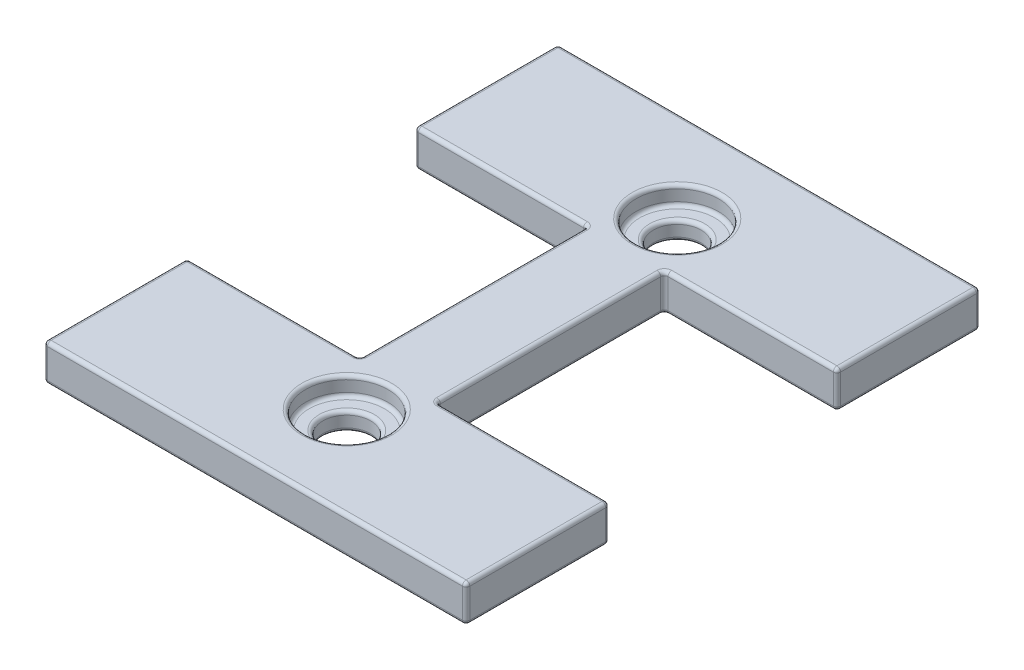
SolidWorks part; units mm, degrees
ref_plane "Front Plane" through (0, 0, 0) normal (0, 0, 1) x (1, 0, 0)
ref_plane "Top Plane" through (0, 0, 0) normal (0, 1, 0) x (1, 0, 0)
ref_plane "Right Plane" through (0, 0, 0) normal (1, 0, 0) x (0, 0, -1)
sketch "Sketch1" plane through (0, 0, 0) normal (0, 1, 0) x (1, 0, 0)
  line L0 (-55, 0) -> (55, 0) construction
  line L1 (-5.75, 7) -> (5.75, 7)
  line L2 (-5.75, 7) -> (-5.75, -7)
  line L3 (-5.75, -7) -> (5.75, -7)
  line L4 (5.75, 7) -> (5.75, -7)
  line L5 (0, -55) -> (0, 55) construction
  dimension "D1" = 14
  dimension "D2" = 7
  dimension "D3" = 11.5
  dimension "D4" = 5.75
extrude "Boss-Extrude1" add sketch "Sketch1" along normal blind 1
sketch "Sketch2" plane through (0, 1, 0) normal (0, 1, 0) x (1, 0, 0)
  line L0 (-0.55, 0) -> (0.55, 0) construction
  line L1 (-9.1867, 3.1) -> (-1.05, 3.1)
  line L2 (-9.1867, 3.1) -> (-9.1867, -3.1)
  line L3 (-9.1867, -3.1) -> (-1.05, -3.1)
  line L4 (-1.05, 3.1) -> (-1.05, -3.1)
  line L5 (1.05, 3.1) -> (10.2161, 3.1)
  line L6 (1.05, 3.1) -> (1.05, -3.1)
  line L7 (1.05, -3.1) -> (10.2161, -3.1)
  line L8 (10.2161, 3.1) -> (10.2161, -3.1)
  line L9 (0, -0.55) -> (0, 0.55) construction
  dimension "D1" = 6.2
  dimension "D2" = 6.2
  dimension "D3" = 3.1
  dimension "D4" = 3.1
  dimension "D5" = 2.1
  dimension "D6" = 1.05
extrude "Cut-Extrude1" cut sketch "Sketch2" against normal blind 1
sketch "Sketch3" plane through (0, 1, 0) normal (0, 1, 0) x (1, 0, 0)
  line L0 (0, -0.55) -> (0, 0.55) construction
  line L1 (-0.55, 0) -> (0.55, 0) construction
  circle A0 centre (0, 4.5) radius 1.125
  circle A1 centre (0, -4.5) radius 1.125
  dimension "D1" = 2.25
  dimension "D2" = 2.25
  dimension "D3" = 9
  dimension "D4" = 4.5
extrude "Cut-Extrude2" cut sketch "Sketch3" against normal blind 0.5
sketch "Sketch4" plane through (0, 0.5, 0) normal (0, 1, 0) x (1, 0, 0)
  circle A0 centre (0, 4.5) radius 0.65
  circle A1 centre (0, -4.5) radius 0.65
  dimension "D1" = 1.3
  dimension "D2" = 1.3
extrude "Cut-Extrude3" cut sketch "Sketch4" against normal blind 0.5
fillet "Fillet1" radius 0.1 44 edges at (3.4, 0, -3.1) (-3.4, 0, 3.1) (-5.75, 0.5, 7) (5.75, 0.5, 7) (5.75, 0.5, -7) (-5.75, 0.5, -7) (0, 1, -7) (5.75, 1, 5.05) (5.75, 1, -5.05) (0, 1, 7) (-5.75, 1, -5.05) (-5.75, 1, 5.05) (0, 0, -7) (5.75, 0, 5.05) (5.75, 0, -5.05) (0, 0, 7) (-5.75, 0, -5.05) (-5.75, 0, 5.05) (-5.75, 0.5, -3.1) (-5.75, 0.5, 3.1) (-1.05, 0.5, -3.1) (-1.05, 0.5, 3.1) (-3.4, 0, -3.1) (-1.05, 0, 0) (-3.4, 1, -3.1) (-1.05, 1, 0) (-3.4, 1, 3.1) (5.75, 0.5, -3.1) (5.75, 0.5, 3.1) (1.05, 0.5, -3.1) (1.05, 0.5, 3.1) (3.4, 0, 3.1) (1.05, 0, 0) (3.4, 1, -3.1) (3.4, 1, 3.1) (1.05, 1, 0) (0, 0.5, -3.375) (0, 1, -3.375) (0, 0.5, 5.625) (0, 1, 5.625) (0, 0, -3.85) (0, 0.5, -3.85) (0, 0, 5.15) (0, 0.5, 5.15)
